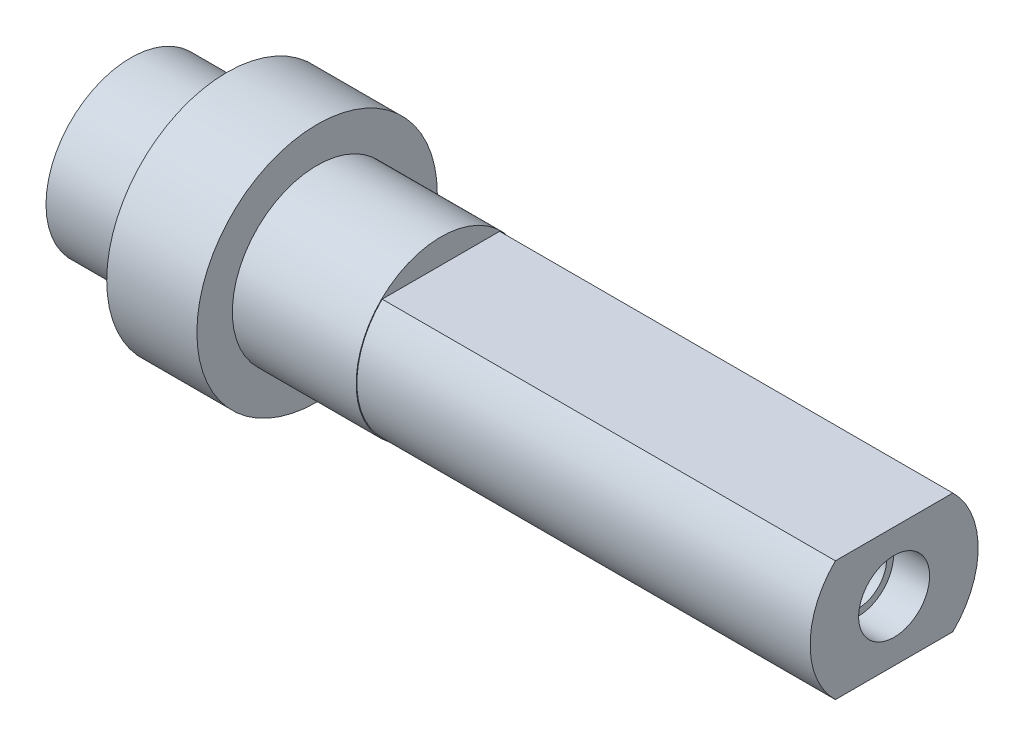
SolidWorks part; units mm, degrees
ref_plane "前视基准面" through (0, 0, 0) normal (0, 0, 1) x (1, 0, 0)
ref_plane "上视基准面" through (0, 0, 0) normal (0, 1, 0) x (1, 0, 0)
ref_plane "右视基准面" through (0, 0, 0) normal (1, 0, 0) x (0, 0, -1)
sketch "草图2" plane through (0, 0, 0) normal (1, 0, 0) x (0, 0, -1)
  circle A0 centre (0, 0) radius 5
  dimension "D1" = 10
extrude "凸台-拉伸1" add sketch "草图2" along normal blind 3.75
sketch "草图3" plane through (0, 0, 0) normal (-1, 0, 0) x (0, 0, 1)
  circle A0 centre (0, 0) radius 3.525
  dimension "D1" = 7.05
extrude "凸台-拉伸2" add sketch "草图3" along normal blind 4
sketch "草图4" plane through (3.75, 0, 0) normal (1, 0, 0) x (0, 0, -1)
  circle A0 centre (0, 0) radius 3.525
  dimension "D1" = 7.05
extrude "凸台-拉伸3" add sketch "草图4" along normal blind 24
sketch "草图5" plane through (3.75, 0, 0) normal (1, 0, 0) x (0, 0, -1)
  line L1 (-6.3937, 2.5) -> (6.3937, 2.5)
  line L2 (-6.3937, 2.5) -> (-6.3937, -2.5)
  line L3 (-6.3937, -2.5) -> (6.3937, -2.5)
  line L4 (6.3937, 2.5) -> (6.3937, -2.5)
  line L5 (-6.3937, 2.5) -> (6.3937, -2.5) construction
  line L6 (-6.3937, -2.5) -> (6.3937, 2.5) construction
  point P0 (0, 0)
  dimension "D1" = 5
extrude "切除-拉伸1" cut sketch "草图5" along normal blind 19.08 from offset 5.15 flip side to cut
sketch "草图6" plane through (27.75, 0, 0) normal (1, 0, 0) x (0, 0, -1)
  circle A0 centre (0, 0) radius 1.19
  dimension "D1" = 2.38
extrude "切除-拉伸2" cut sketch "草图6" against normal blind 8
sketch "草图7" plane through (27.75, 0, 0) normal (1, 0, 0) x (0, 0, -1)
  circle A0 centre (0, 0) radius 1.475
  dimension "D1" = 2.95
extrude "切除-拉伸3" cut sketch "草图7" against normal blind 1.5
sketch "草图8" plane through (27.75, 0, 0) normal (1, 0, 0) x (0, 0, -1)
  circle A0 centre (0, 0) radius 3.495
  dimension "D1" = 6.99
extrude "切除-拉伸5" cut sketch "草图8" against normal up to surface (18.85 mm away) flip side to cut up to face at (8.9, 3.0125, 0)
